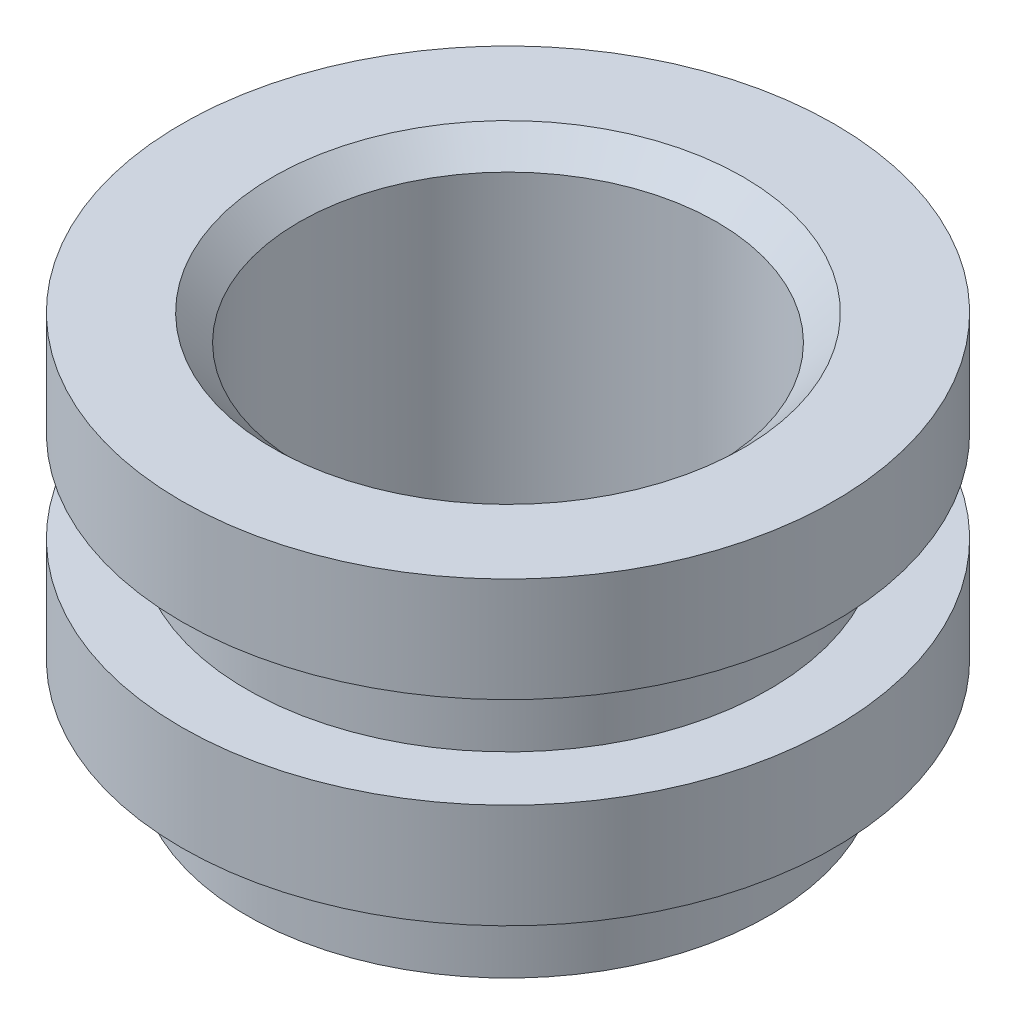
SolidWorks part; units mm, degrees
ref_plane "前视基准面" through (0, 0, 0) normal (0, 0, 1) x (1, 0, 0)
ref_plane "上视基准面" through (0, 0, 0) normal (0, 1, 0) x (1, 0, 0)
ref_plane "右视基准面" through (0, 0, 0) normal (1, 0, 0) x (0, 0, -1)
sketch "草图1" plane through (0, 0, 0) normal (0, 0, 1) x (1, 0, 0)
  line L0 (0, -2.6047) -> (0, 3.6552) construction
  line L1 (-0.8, 0.9584) -> (-1.25, 0.9584)
  line L2 (-1.25, 0.9584) -> (-1.25, 0.5584)
  line L3 (-1.25, 0.5584) -> (-1, 0.5584)
  line L4 (-1, 0.5584) -> (-1, 0.2084)
  line L5 (-0.8, -0.5416) -> (-1, -0.5416)
  line L10 (-0.8, -0.5416) -> (-0.8, 0.9584)
  line L11 (-1, 0.2084) -> (-1.25, 0.2084)
  line L12 (-1.25, 0.2084) -> (-1.25, -0.1916)
  line L13 (-1.25, -0.1916) -> (-1, -0.1916)
  line L14 (-1, -0.1916) -> (-1, -0.5416)
  dimension "D1" = 1.25
  dimension "D2" = 1.5
  dimension "D3" = 0.4
  dimension "D4" = 0.8
  dimension "D5" = 1
revolve "旋转1" add sketch "草图1" angle 360 about L0
chamfer "倒角1" distance 0.1 angle 45 2 edges at (0, 0.9584, -0.8) (0, -0.5416, -0.8)
